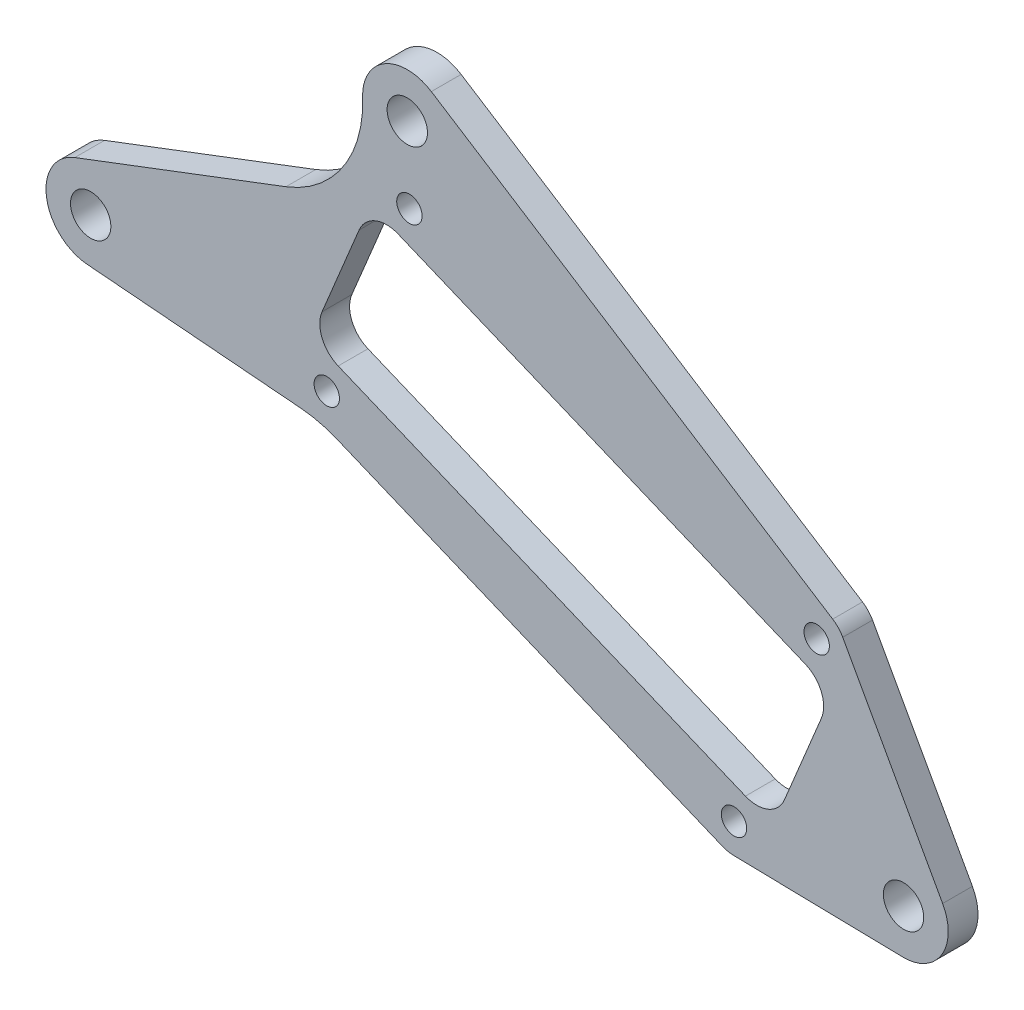
SolidWorks part; units mm, degrees
material "ABS PC"
ref_plane "Front Plane" through (0, 0, 0) normal (0, 0, 1) x (1, 0, 0)
ref_plane "Top Plane" through (0, 0, 0) normal (0, 1, 0) x (1, 0, 0)
ref_plane "Right Plane" through (0, 0, 0) normal (1, 0, 0) x (0, 0, -1)
sketch "Sketch1" plane through (0, 0, 0) normal (0, 0, 1) x (1, 0, 0)
  line L0 (80.1722, 1.0948) -> (90.8214, -18.1613)
  line L1 (86.5572, -25.2276) -> (68.5193, -24.8619)
  line L2 (33.9785, 17.5615) -> (68.5836, -21.6875) construction
  line L3 (33.9785, 17.5615) -> (25.1684, -3.6842) construction
  line L4 (29.5735, 6.9386) -> (51.2811, -2.063) construction
  line L5 (23.9522, -6.6171) -> (67.3674, -24.6204)
  line L6 (-0.3944, -4.7461) -> (24.9055, -6.8483)
  line L7 (-1.6929, 4.4514) -> (30.8862, 16.8417)
  line L8 (29.1149, 24.4508) -> (30.8862, 16.8417)
  line L9 (36.3158, 29.545) -> (79.102, 2.2345)
  line L10 (72.7326, -19.9709) -> (23.4517, 0.4648)
  line L11 (72.7326, -19.9709) -> (79.1104, -4.5908)
  line L12 (23.4517, 0.4648) -> (29.8295, 15.8449)
  line L13 (79.1104, -4.5908) -> (29.8295, 15.8449)
  line L14 (72.7326, -19.9709) -> (29.8295, 15.8449) construction
  line L15 (23.4517, 0.4648) -> (79.1104, -4.5908) construction
  circle A0 centre (0, 0) radius 4.7625
  circle A1 centre (86.6537, -20.4661) radius 4.7625
  circle A2 centre (33.7534, 25.5306) radius 4.7625
  circle A3 centre (33.9785, 17.5615) radius 3.175
  circle A4 centre (77.3937, -0.4418) radius 3.175
  circle A5 centre (68.5836, -21.6875) radius 3.175
  circle A6 centre (25.1684, -3.6842) radius 3.175
  point P27 (23.9522, 0)
  point P28 (29.5735, 6.9386)
  dimension "D1" = 9.525
  dimension "D4" = 6.35
  dimension "D2" = 3.175
  dimension "D3" = 3.175
extrude "Boss-Extrude1" add sketch "Sketch1" along normal blind 3.175 contours A0 | A6 | A3 | A2 | A4 | A1 | A5 | A6 L6 L5 A5 L1 A1 L0 A4 L9 A2 L8 A3 L7 A0 | A6 L5 L6 | A4 L9 A2 L8 A3 L13 | A6 L6 L5 A5 L10 | A5 L1 A1 L0 A4 L11
fillet "Fillet1" radius 3.175 4 edges at (72.7326, -19.9709, 1.5875) (79.1104, -4.5908, 1.5875) (23.4517, 0.4648, 1.5875) (29.8295, 15.8449, 1.5875)
hole_wizard "#6 Clearance Hole1" positions "Sketch2" profile "Sketch3" hole size "#6" standard "ANSI Inch" end condition through all
sketch "Sketch2" plane through (0, 0, 3.175) normal (0, 0, 1) x (1, 0, 0)
  point P0 (0, 0)
  point P3 (33.7534, 25.5306)
  point P6 (86.6537, -20.4661)
sketch "Sketch3" plane through (0, 0, 3.175) normal (1, 0, 0) x (0, -1, 0)
  line L0 (0, 0) -> (0, 3.175)
  line L1 (0, 3.175) -> (2.1526, 3.175)
  line L2 (2.1526, 3.175) -> (2.1526, 0)
  line L5 (2.1526, 0) -> (0, 0)
  line L11 (0, -6.35) -> (0, 107.95) construction
  dimension "Thru Hole Dia." = 4.3053
  dimension "Thru Hole Depth" = 3.175
hole_wizard "#2 Clearance Hole1" positions "Sketch4" profile "Sketch5" hole size "#2" standard "ANSI Inch" end condition through all
sketch "Sketch4" plane through (0, 0, 3.175) normal (0, 0, 1) x (1, 0, 0)
  point P1 (33.9785, 17.5615)
  point P4 (77.3937, -0.4418)
  point P7 (68.5836, -21.6875)
  point P10 (25.1684, -3.6842)
sketch "Sketch5" plane through (33.9785, 17.5615, 3.175) normal (1, 0, 0) x (0, -1, 0)
  line L0 (0, 0) -> (0, 3.175)
  line L1 (0, 3.175) -> (1.3525, 3.175)
  line L2 (1.3525, 3.175) -> (1.3525, 0)
  line L5 (1.3525, 0) -> (0, 0)
  line L11 (0, -6.35) -> (0, 107.95) construction
  dimension "Thru Hole Dia." = 2.7051
  dimension "Thru Hole Depth" = 3.175
fillet "Fillet2" radius 12.7 2 edges at (24.4108, -6.8072, 1.5875) (30.8862, 16.8417, 1.5875)
